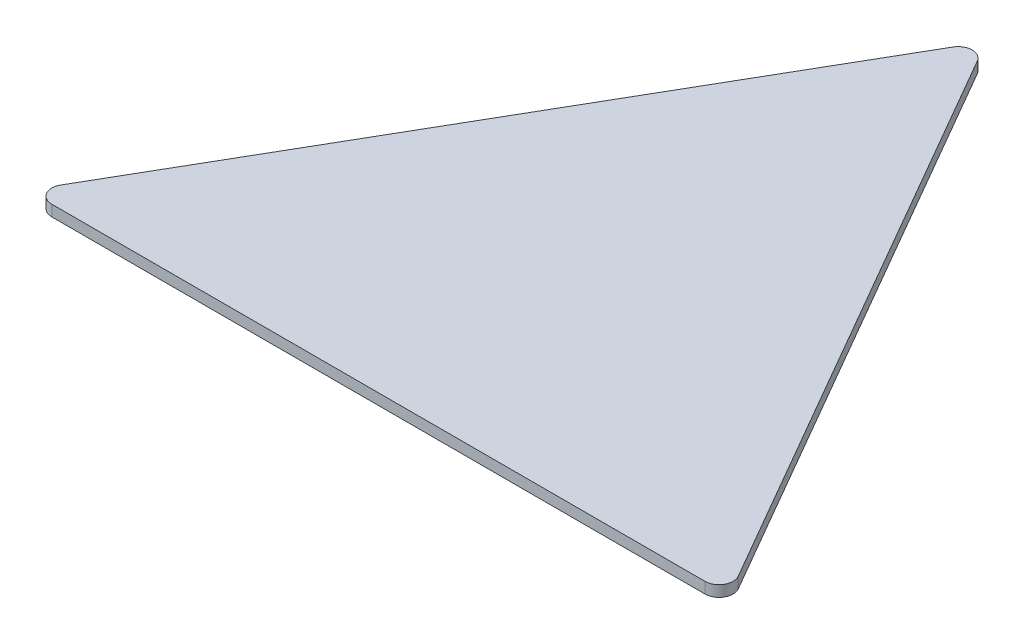
SolidWorks part; units mm, degrees
ref_plane "Front Plane" through (0, 0, 0) normal (0, 0, 1) x (1, 0, 0)
ref_plane "Top Plane" through (0, 0, 0) normal (0, 1, 0) x (1, 0, 0)
ref_plane "Right Plane" through (0, 0, 0) normal (1, 0, 0) x (0, 0, -1)
sketch "Sketch1" plane through (0, 0, 0) normal (0, 1, 0) x (1, 0, 0)
  line L1 (0, 146.647) -> (-127, -73.3235)
  line L2 (-127, -73.3235) -> (127, -73.3235)
  line L3 (127, -73.3235) -> (0, 146.647)
  circle A0 centre (0, 0) radius 73.3235 construction
  dimension "D1" = 254
extrude "Boss-Extrude1" add sketch "Sketch1" along normal blind 3.9878
fillet "Fillet1" radius 5.08 3 edges at (-127, 1.9939, 73.3235) (0, 1.9939, -146.647) (127, 1.9939, 73.3235)
